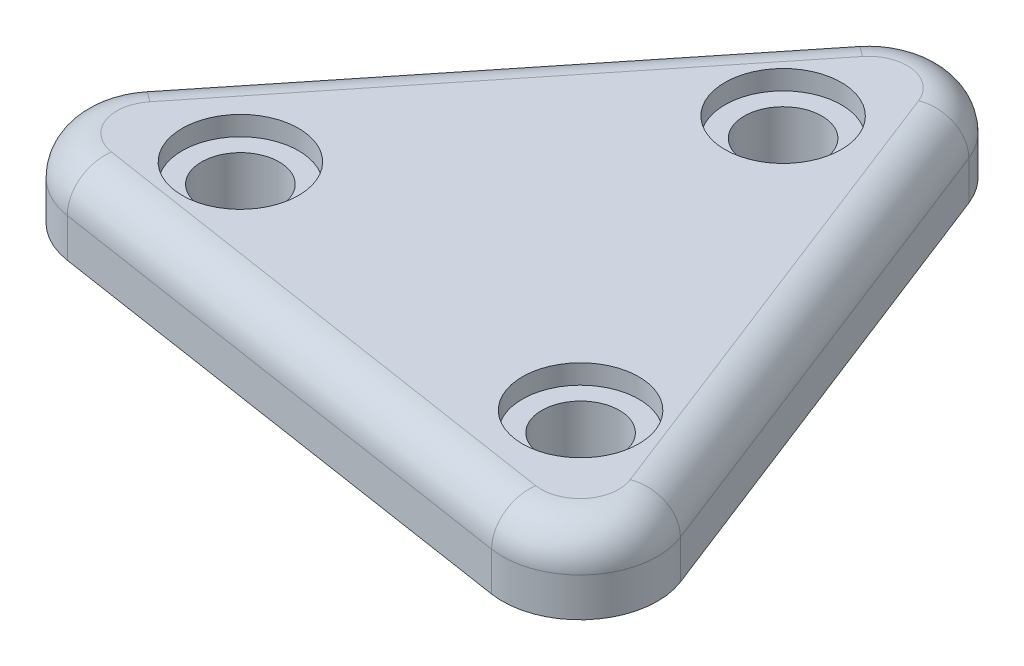
SolidWorks part; units mm, degrees
ref_plane "Front Plane" through (0, 0, 0) normal (0, 0, 1) x (1, 0, 0)
ref_plane "Top Plane" through (0, 0, 0) normal (0, 1, 0) x (1, 0, 0)
ref_plane "Right Plane" through (0, 0, 0) normal (1, 0, 0) x (0, 0, -1)
sketch "Sketch1" plane through (0, 0, 0) normal (0, 1, 0) x (1, 0, 0)
  line L1 (0.6704, 5.7344) -> (-5.3014, -2.2866) construction
  line L2 (-5.3014, -2.2866) -> (4.631, -3.4478) construction
  line L3 (4.631, -3.4478) -> (0.6704, 5.7344) construction
  line L4 (1.7502, 11.4136) -> (-10.7596, -4.191)
  line L5 (-10.7596, -4.191) -> (9.0093, -7.2226)
  line L6 (9.0093, -7.2226) -> (1.7502, 11.4136)
  circle A0 centre (0, 0) radius 2.8868 construction
  circle A1 centre (0.6704, 5.7344) radius 1
  circle A2 centre (4.631, -3.4478) radius 1
  circle A3 centre (-5.3014, -2.2866) radius 1
  circle A4 centre (0, 0) radius 5.7735 construction
extrude "Boss-Extrude1" add sketch "Sketch1" along normal blind 2
fillet "Fillet1" radius 2 3 edges at (1.7502, 1, -11.4136) (9.0093, 1, 7.2226) (-10.7596, 1, 4.191)
fillet "Fillet2" radius 1 6 edges at (-8.896, 2, 3.4651) (-4.5047, 2, -3.6113) (1.4471, 2, -9.4367) (5.3798, 2, -2.0955) (7.4489, 2, 5.9716) (-0.8751, 2, 5.7068)
sketch "Sketch2" plane through (0, 2, 0) normal (0, 1, 0) x (1, 0, 0)
  circle A0 centre (0.6704, 5.7344) radius 1.5
  circle A1 centre (-5.3014, -2.2866) radius 1.5
  circle A2 centre (4.631, -3.4478) radius 1.5
extrude "Cut-Extrude1" cut sketch "Sketch2" against normal blind 0.5
